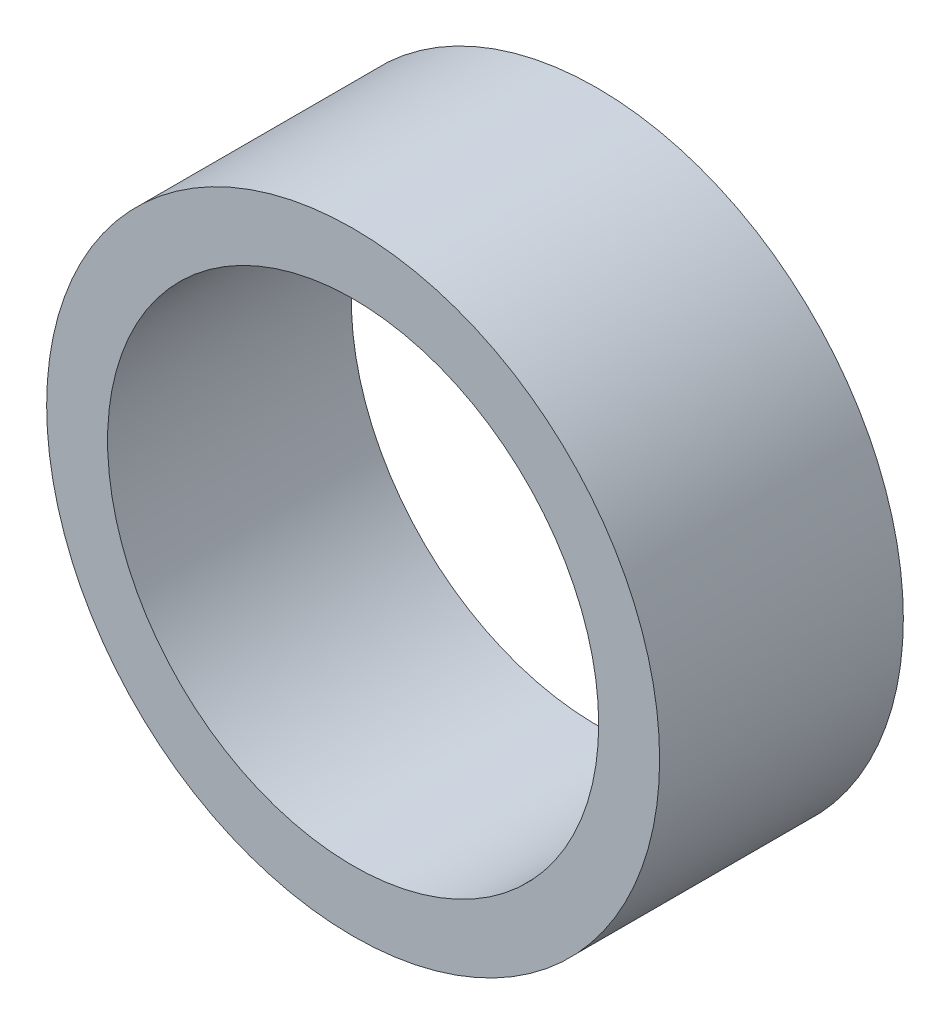
SolidWorks part; units mm, degrees
ref_plane "Front Plane" through (0, 0, 0) normal (0, 0, 1) x (1, 0, 0)
ref_plane "Top Plane" through (0, 0, 0) normal (0, 1, 0) x (1, 0, 0)
ref_plane "Right Plane" through (0, 0, 0) normal (1, 0, 0) x (0, 0, -1)
sketch "Sketch1" plane through (0, 0, 0) normal (0, 0, 1) x (1, 0, 0)
  circle A0 centre (0, 0) radius 4.03
  dimension "D1" = 8.06
extrude "Extrude-Thin1" add sketch "Sketch1" along normal blind 4 thin
